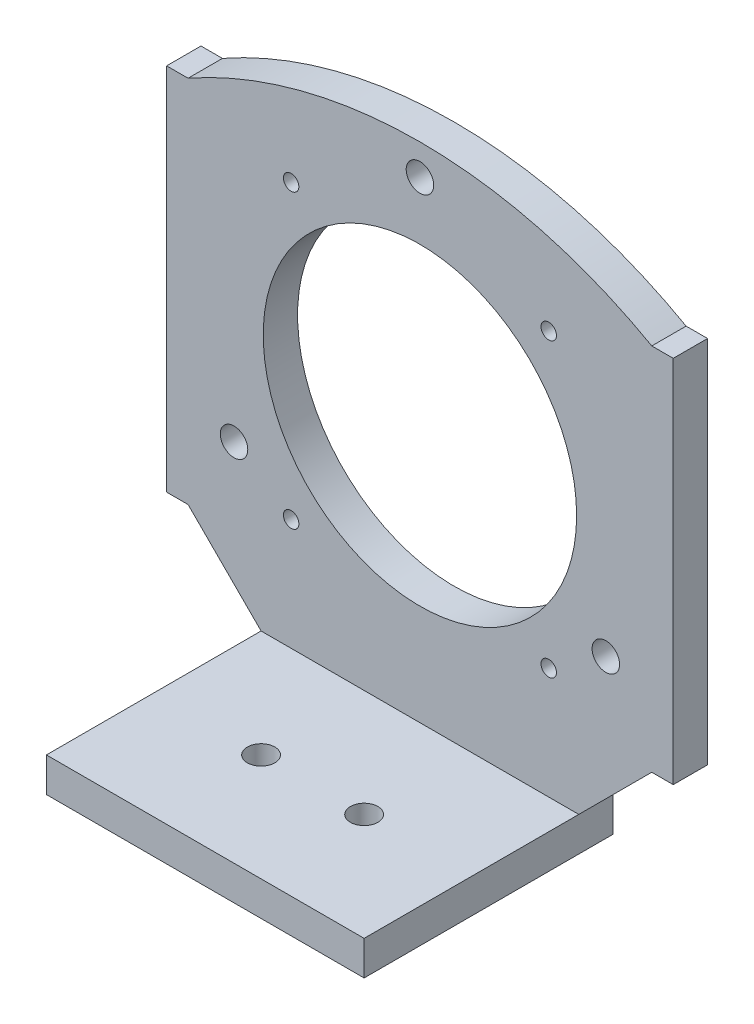
SolidWorks part; units mm, degrees
ref_plane "前视基准面" through (0, 0, 0) normal (0, 0, 1) x (1, 0, 0)
ref_plane "上视基准面" through (0, 0, 0) normal (0, 1, 0) x (1, 0, 0)
ref_plane "右视基准面" through (0, 0, 0) normal (1, 0, 0) x (0, 0, -1)
other "Configuration Table"
sketch "草图1" plane through (0, 0, 0) normal (0, 0, 1) x (1, 0, 0)
  line L0 (0, 72.3434) -> (0, -65.8205) construction
  line L1 (-18.5, -34) -> (18.5, -34)
  line L2 (18.5, -34) -> (18.5, -30)
  line L3 (18.5, -30) -> (27, -21.5)
  line L4 (27, -21.5) -> (29.5, -21.5)
  line L5 (29.5, -21.5) -> (29.5, 21.5)
  line L6 (29.5, 21.5) -> (27, 21.5)
  line L7 (-18.5, -34) -> (-18.5, -30)
  line L8 (-18.5, -30) -> (-27, -21.5)
  line L9 (-27, -21.5) -> (-29.5, -21.5)
  line L10 (-29.5, -21.5) -> (-29.5, 21.5)
  line L11 (-29.5, 21.5) -> (-27, 21.5)
  line L12 (-51.7719, 0) -> (54.8246, 0) construction
  circle A0 centre (0, 0) radius 18.25
  arc A1 (-27, 21.5) -> (27, 21.5) centre (0, -26.4166) cw
  circle A2 centre (0, 0) radius 25 construction
  circle A3 centre (0, 25) radius 1.6
  circle A4 centre (21.6506, -12.5) radius 1.6
  circle A5 centre (-21.6506, -12.5) radius 1.6
  circle A6 centre (-15, 17) radius 0.9
  circle A7 centre (15, 17) radius 0.9
  circle A8 centre (15, -17) radius 0.9
  circle A9 centre (-15, -17) radius 0.9
  point P13 (0, -34)
  point P30 (0, 0)
  dimension "D1" = 36.5
  dimension "D8" = 55
  dimension "D9" = 50
  dimension "D10" = 3.2
  dimension "D12" = 34
  dimension "D13" = 30
  dimension "D14" = 1.8
  dimension "D2" = 34
  dimension "D3" = 4
  dimension "D4" = 37
  dimension "D5" = 59
  dimension "D6" = 45
  dimension "D7" = 43
  dimension "D11" = 3
extrude "凸台-拉伸1" add sketch "草图1" along normal blind 4
sketch "草图2" plane through (0, 0, 4) normal (0, 0, 1) x (1, 0, 0)
  line L0 (18.5, -30) -> (-18.5, -30)
  line L1 (-18.5, -30) -> (-18.5, -34)
  line L2 (-18.5, -34) -> (18.5, -34)
  line L3 (18.5, -34) -> (18.5, -30)
extrude "凸台-拉伸2" add sketch "草图2" along normal blind 25
sketch "草图3" plane through (0, -30, 0) normal (0, 1, 0) x (1, 0, 0)
  line L0 (-21.4849, -16.5) -> (21.2664, -16.5) construction
  line L1 (-27, -4) -> (27, -4) construction
  line L2 (0, 5.1459) -> (0, -35.8574) construction
  circle A0 centre (-6, -16.5) radius 1.6
  circle A1 centre (6, -16.5) radius 1.6
  dimension "D2" = 12
  dimension "D3" = 3.2
  dimension "D1" = 12.5
extrude "切除-拉伸1" cut sketch "草图3" against normal through all
